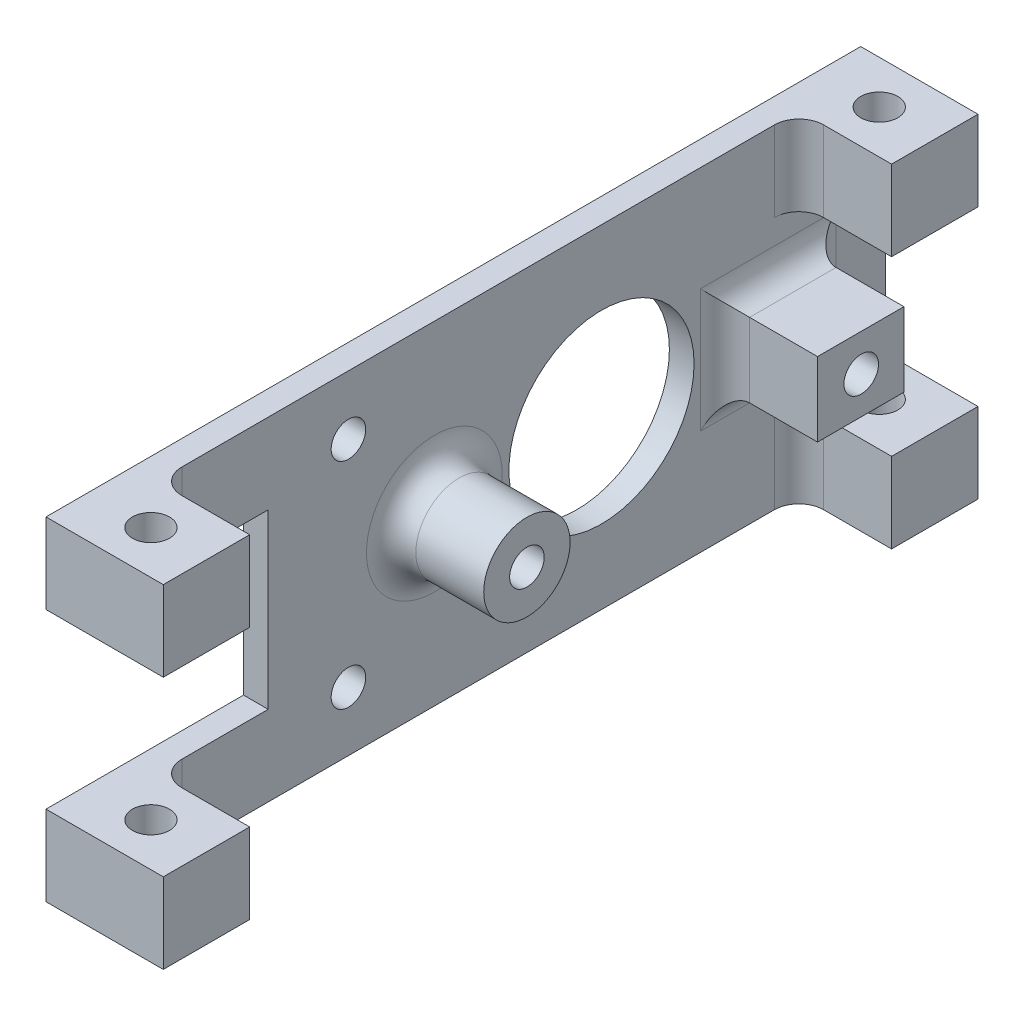
SolidWorks part; units mm, degrees
ref_plane "Front Plane" through (0, 0, 0) normal (0, 0, 1) x (1, 0, 0)
ref_plane "Top Plane" through (0, 0, 0) normal (0, 1, 0) x (1, 0, 0)
ref_plane "Right Plane" through (0, 0, 0) normal (1, 0, 0) x (0, 0, -1)
sketch "Sketch1" plane through (0, 0, 0) normal (1, 0, 0) x (0, 0, -1)
  line L1 (-33, 13.5) -> (33, 13.5)
  line L2 (-33, 13.5) -> (-33, -13.5)
  line L3 (-33, -13.5) -> (33, -13.5)
  line L4 (33, 13.5) -> (33, -13.5)
  dimension "D1" = 66
  dimension "D2" = 27
  dimension "D3" = 13.5
  dimension "D4" = 33
extrude "Boss-Extrude1" add sketch "Sketch1" along normal blind 2
sketch "Sketch2" plane through (2, 0, 0) normal (1, 0, 0) x (0, 0, -1)
  line L0 (33, -13.5) -> (33, 13.5) construction
  circle A0 centre (10, 0) radius 7.5
  dimension "D1" = 15
  dimension "D2" = 23
extrude "Cut-Extrude1" cut sketch "Sketch2" against normal blind 2
sketch "Sketch3" plane through (2, 0, 0) normal (1, 0, 0) x (0, 0, -1)
  line L0 (-33, -13.5) -> (33, -13.5) construction
  line L1 (33, 13.5) -> (26, 13.5)
  line L2 (33, 13.5) -> (33, -13.5)
  line L3 (33, -13.5) -> (26, -13.5)
  line L4 (26, 13.5) -> (26, 3)
  line L5 (26, -3) -> (26, -13.5)
  line L6 (26, 3) -> (20, 3)
  line L8 (26, -3) -> (20, -3)
  line L9 (20, 3) -> (20, -3)
  dimension "D1" = 7
  dimension "D2" = 6
  dimension "D3" = 6
  dimension "D4" = 3
extrude "Boss-Extrude2" add sketch "Sketch3" along normal blind 7.5
sketch "Sketch4" plane through (0, 13.5, 0) normal (0, 1, 0) x (1, 0, 0)
  line L0 (9.5, 33) -> (0, 33) construction
  line L1 (0, 33) -> (0, -33) construction
  circle A0 centre (5, 29.5) radius 1.5
  dimension "D1" = 3
  dimension "D2" = 3.5
  dimension "D3" = 5
extrude "Cut-Extrude2" cut sketch "Sketch4" against normal blind 31
sketch "Sketch5" plane through (9.5, 0, 0) normal (1, 0, 0) x (0, 0, -1)
  line L0 (20, 3) -> (20, -3) construction
  circle A0 centre (23.54, 0) radius 1.4
  dimension "D1" = 2.8
  dimension "D2" = 3.54
extrude "Cut-Extrude3" cut sketch "Sketch5" against normal blind 31
sketch "Sketch6" plane through (2, 0, 0) normal (1, 0, 0) x (0, 0, -1)
  line L0 (-33, -13.5) -> (26, -13.5) construction
  line L1 (-33, 13.5) -> (-26, 13.5)
  line L2 (-33, 13.5) -> (-33, -13.5)
  line L3 (-33, -13.5) -> (-26, -13.5)
  line L4 (-26, 13.5) -> (-26, -13.5)
  dimension "D1" = 7
extrude "Boss-Extrude3" add sketch "Sketch6" along normal blind 7.5
sketch "Sketch7" plane through (0, 13.5, 0) normal (0, 1, 0) x (1, 0, 0)
  line L0 (9.5, -33) -> (0, -33) construction
  line L1 (0, 33) -> (0, -33) construction
  circle A0 centre (5, -29.5) radius 1.5
  dimension "D1" = 3
  dimension "D2" = 3.5
  dimension "D3" = 5
extrude "Cut-Extrude4" cut sketch "Sketch7" against normal blind 33.5
sketch "Sketch8" plane through (2, 0, 0) normal (1, 0, 0) x (0, 0, -1)
  line L0 (-33, 13.5) -> (-33, -13.5) construction
  line L1 (-33, 7) -> (-17, 7)
  line L2 (-33, 7) -> (-33, -7)
  line L3 (-33, -7) -> (-17, -7)
  line L4 (-17, 7) -> (-17, -7)
  dimension "D1" = 14
  dimension "D2" = 7
  dimension "D3" = 16
extrude "Cut-Extrude5" cut sketch "Sketch8" along normal mid plane 31.5
sketch "Sketch9" plane through (2, 0, 0) normal (1, 0, 0) x (0, 0, -1)
  line L0 (33, -13.5) -> (33, 13.5) construction
  line L1 (-26, -13.5) -> (26, -13.5) construction
  circle A0 centre (-10.5, -8.7) radius 1.4
  dimension "D1" = 43.5
  dimension "D2" = 4.8
  dimension "D3" = 2.8
extrude "Cut-Extrude6" cut sketch "Sketch9" against normal blind 31.5
mirror "Mirror1" about plane through (0, 0, 0) normal (0, 1, 0) of "Cut-Extrude6"
sketch "Sketch10" plane through (2, 0, 0) normal (1, 0, 0) x (0, 0, -1)
  circle A0 centre (-3.54, 0) radius 3.5
  circle A1 centre (10, 0) radius 7.5 construction
  dimension "D1" = 7
  dimension "D2" = 13.54
extrude "Boss-Extrude4" add sketch "Sketch10" along normal up to surface (7.5 mm away) up to face at (9.5, 0, -24.94)
sketch "Sketch11" plane through (9.5, 0, 0) normal (1, 0, 0) x (0, 0, -1)
  circle A0 centre (-3.54, 0) radius 1.4
  dimension "D1" = 2.8
extrude "Cut-Extrude7" cut sketch "Sketch11" against normal blind 9.5
sketch "Sketch12" plane through (9.5, 0, 0) normal (1, 0, 0) x (0, 0, -1)
  line L0 (26, -3) -> (26, -13.5) construction
  line L1 (26, -7) -> (33, -7)
  line L2 (26, -7) -> (26, -3)
  line L3 (26, -3) -> (27, -3)
  line L4 (33, -7) -> (33, -3)
  line L5 (33, -13.5) -> (33, 13.5) construction
  line L7 (26, 3) -> (27, 3)
  line L8 (26, 3) -> (26, 7)
  line L9 (26, 7) -> (33, 7)
  line L10 (33, 3) -> (33, 7)
  line L12 (27, 3) -> (27, -3)
  line L14 (33, 3) -> (33, -3)
  dimension "D1" = 6
extrude "Cut-Extrude8" cut sketch "Sketch12" against normal up to surface (7.5 mm away) up to face at (2, 8.7, 9.1)
fillet "Fillet1" radius 2 9 edges at (2, 0, 0.04) (2, -10.25, 26) (2, 0, -20) (2, -3, -23.5) (2, 3, -23.5) (2, 10.25, 26) (2, 0, -27)
